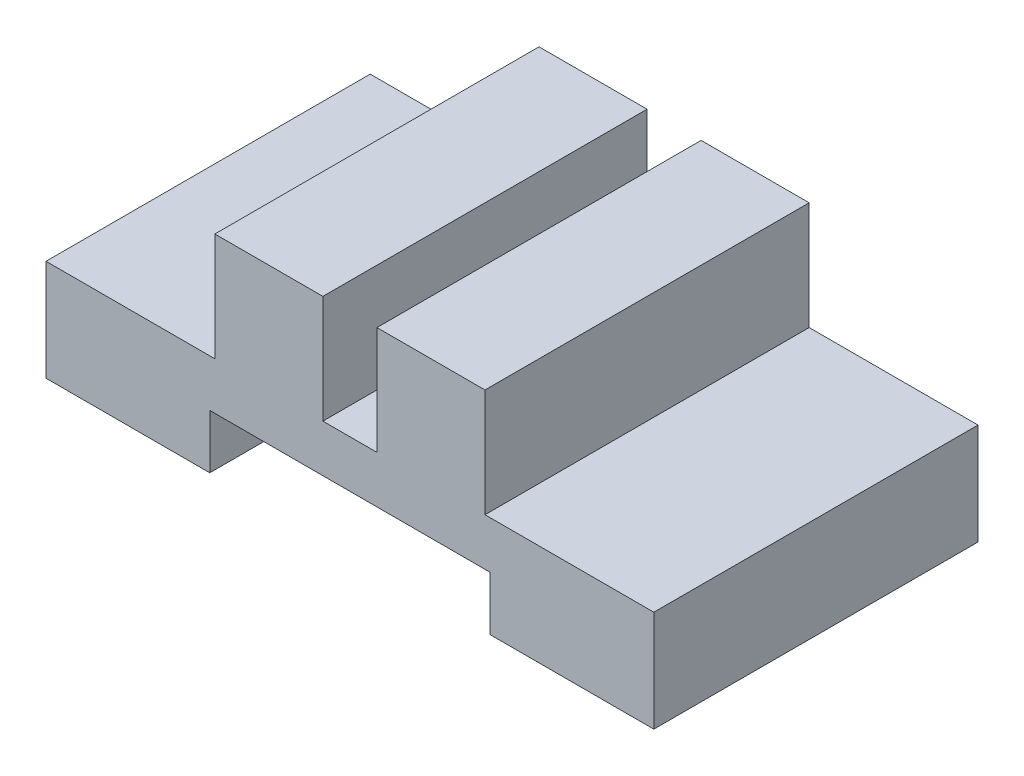
SolidWorks part; units mm, degrees
ref_plane "Front Plane" through (0, 0, 0) normal (0, 0, 1) x (1, 0, 0)
ref_plane "Top Plane" through (0, 0, 0) normal (0, 1, 0) x (1, 0, 0)
ref_plane "Right Plane" through (0, 0, 0) normal (1, 0, 0) x (0, 0, -1)
sketch "Sketch1" plane through (0, 0, 0) normal (0, 1, 0) x (1, 0, 0)
  line L1 (-4.5, -2.4) -> (4.5, -2.4)
  line L2 (-4.5, -2.4) -> (-4.5, 2.4)
  line L3 (-4.5, 2.4) -> (4.5, 2.4)
  line L4 (4.5, -2.4) -> (4.5, 2.4)
  line L5 (-4.5, -2.4) -> (4.5, 2.4) construction
  line L6 (-4.5, 2.4) -> (4.5, -2.4) construction
  point P0 (0, 0)
  dimension "D1" = 4.8
  dimension "D2" = 9
extrude "Boss-Extrude1" add sketch "Sketch1" along normal blind 1.5
sketch "Sketch2" plane through (0, 0, 0) normal (0, -1, 0) x (-1, 0, 0)
  line L0 (4.5, -2.4) -> (-4.5, -2.4) construction
  line L1 (2.075, 2.4) -> (-2.075, 2.4)
  line L2 (2.075, 2.4) -> (2.075, -2.4)
  line L3 (2.075, -2.4) -> (-2.075, -2.4)
  line L4 (-2.075, 2.4) -> (-2.075, -2.4)
  line L5 (2.075, 2.4) -> (-2.075, -2.4) construction
  line L6 (2.075, -2.4) -> (-2.075, 2.4) construction
  point P0 (0, 0)
  dimension "D1" = 4.15
extrude "Cut-Extrude1" cut sketch "Sketch2" against normal blind 0.8
sketch "Sketch3" plane through (0, 1.5, 0) normal (0, 1, 0) x (1, 0, 0)
  line L0 (4.5, 2.4) -> (-4.5, 2.4) construction
  line L1 (0.4, 2.4) -> (2, 2.4)
  line L2 (0.4, 2.4) -> (0.4, -2.4)
  line L3 (0.4, -2.4) -> (2, -2.4)
  line L4 (2, 2.4) -> (2, -2.4)
  line L5 (-2, -2.4) -> (-0.4, -2.4)
  line L6 (-2, -2.4) -> (-2, 2.4)
  line L7 (-2, 2.4) -> (-0.4, 2.4)
  line L8 (-0.4, -2.4) -> (-0.4, 2.4)
  line L9 (-4.5, -2.4) -> (4.5, -2.4) construction
  line L10 (2, 2.4) -> (-2, -2.4) construction
  point P12 (0, 2.4)
  point P13 (0, 0)
  dimension "D1" = 1.6
  dimension "D2" = 0.8
extrude "Boss-Extrude2" add sketch "Sketch3" along normal blind 1.6
